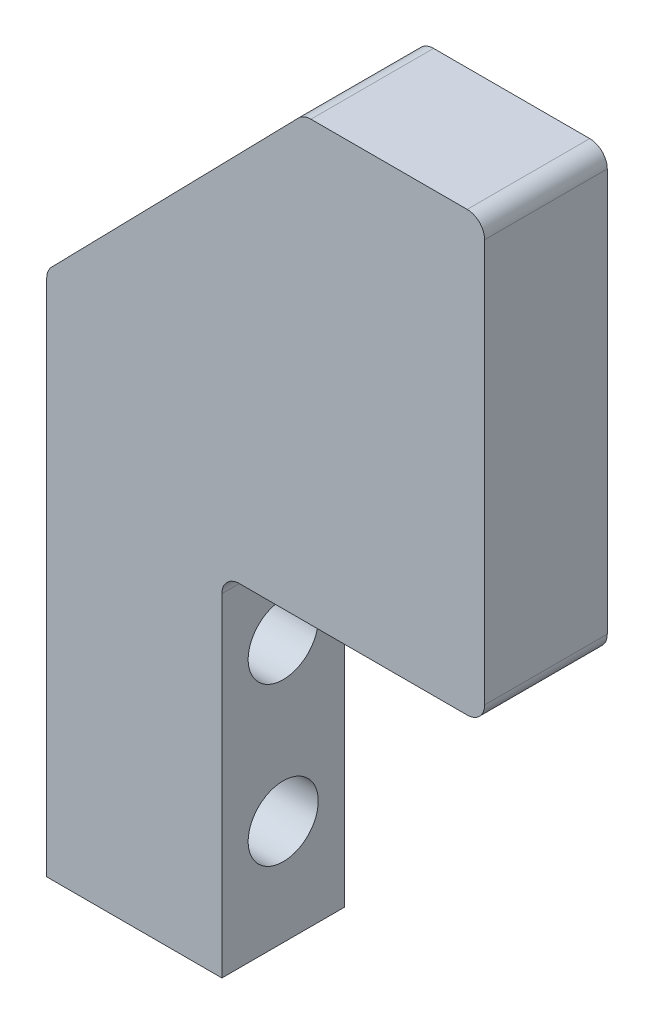
SolidWorks part; units mm, degrees
ref_plane "Front Plane" through (0, 0, 0) normal (0, 0, 1) x (1, 0, 0)
ref_plane "Top Plane" through (0, 0, 0) normal (0, 1, 0) x (1, 0, 0)
ref_plane "Right Plane" through (0, 0, 0) normal (1, 0, 0) x (0, 0, -1)
sketch "Sketch1" plane through (0, 0, 0) normal (0, 0, 1) x (1, 0, 0)
  line L0 (-187.207, 37.0865) -> (-187.207, -258.8379)
  line L1 (-36.3759, 191.1621) -> (52.793, 191.1621)
  line L3 (-187.207, -258.8379) -> (-87.207, -258.8379)
  line L4 (62.793, 181.1621) -> (62.793, -48.8379)
  line L5 (-87.207, -258.8379) -> (-87.207, -68.8379)
  line L6 (-77.207, -58.8379) -> (52.793, -58.8379)
  line L9 (-43.527, 188.1522) -> (-184.3582, 44.0766)
  arc A0 (62.793, 181.1621) -> (52.793, 191.1621) centre (52.793, 181.1621) ccw
  arc A1 (52.793, -58.8379) -> (62.793, -48.8379) centre (52.793, -48.8379) ccw
  arc A2 (-87.207, -68.8379) -> (-77.207, -58.8379) centre (-77.207, -68.8379) cw
  arc A3 (-187.207, 37.0865) -> (-184.3582, 44.0766) centre (-177.207, 37.0865) cw
  arc A4 (-43.527, 188.1522) -> (-36.3759, 191.1621) centre (-36.3759, 181.1621) cw
extrude "Boss-Extrude1" add sketch "Sketch1" along normal blind 70
sketch "Sketch2" plane through (-87.207, 0, 0) normal (1, 0, 0) x (0, 0, -1)
  circle A0 centre (-35, -108.8379) radius 20
  circle A1 centre (-35, -198.8379) radius 20
extrude "Cut-Extrude1" cut sketch "Sketch2" against normal blind 129
sketch "Sketch3" plane through (0, 0, 70) normal (0, 0, 1) x (1, 0, 0)
  line L0 (62.793, 165.6063) -> (62.793, 165.5345)
  line L1 (62.793, 179.5345) -> (62.793, 172.5345)
  line L2 (62.793, 151.6063) -> (62.793, 151.5345)
  line L3 (62.793, 158.6063) -> (62.793, 158.5345)
  line L4 (62.793, 144.6063) -> (62.793, 144.5345)
  line L5 (62.793, 137.6063) -> (62.793, 137.5345)
  line L6 (62.793, 130.6063) -> (62.793, 130.5345)
  line L7 (62.793, 123.6063) -> (62.793, 123.5345)
  line L8 (62.793, 116.6063) -> (62.793, 116.5345)
  line L9 (62.793, 109.6063) -> (62.793, 109.5345)
  line L10 (62.793, 102.6063) -> (62.793, 102.5345)
  line L12 (62.793, 102.5345) -> (62.793, 97.0704)
  line L13 (62.793, 172.6063) -> (62.793, 172.5345)
  line L14 (62.793, 172.5345) -> (62.793, 165.5345)
  line L15 (62.793, 165.5345) -> (62.793, 158.5345)
  line L16 (62.793, 158.5345) -> (62.793, 151.5345)
  line L17 (62.793, 151.5345) -> (62.793, 144.5345)
  line L18 (62.793, 144.5345) -> (62.793, 137.6063)
  arc A0 (61.793, 177.8024) -> (61.793, 174.3383) centre (62.793, 176.0704) ccw
  arc A1 (61.793, 170.8024) -> (61.793, 167.3383) centre (62.793, 169.0704) ccw
  arc A2 (61.793, 163.8024) -> (61.793, 160.3383) centre (62.793, 162.0704) ccw
  arc A3 (61.793, 156.8024) -> (61.793, 153.3383) centre (62.793, 155.0704) ccw
  arc A4 (61.793, 149.8024) -> (61.793, 146.3383) centre (62.793, 148.0704) ccw
  arc A5 (61.793, 142.8024) -> (61.793, 139.3383) centre (62.793, 141.0704) ccw
  arc A6 (61.793, 135.8024) -> (61.793, 132.3383) centre (62.793, 134.0704) ccw
  arc A7 (61.793, 128.8024) -> (61.793, 125.3383) centre (62.793, 127.0704) ccw
  arc A8 (61.793, 121.8024) -> (61.793, 118.3383) centre (62.793, 120.0704) ccw
  arc A9 (61.793, 114.8024) -> (61.793, 111.3383) centre (62.793, 113.0704) ccw
  arc A10 (61.793, 107.8024) -> (61.793, 104.3383) centre (62.793, 106.0704) ccw
  arc A11 (61.793, 100.8024) -> (62.793, 97.0704) centre (62.793, 99.0704) ccw
  arc A12 (61.793, 177.8024) -> (62.793, 179.5345) centre (60.793, 179.5345) ccw
  arc A13 (62.793, 165.6063) -> (61.793, 167.3383) centre (60.793, 165.6063) ccw
  arc A14 (62.793, 172.5345) -> (61.793, 170.8024) centre (60.793, 172.5345) cw
  arc A15 (61.793, 174.3383) -> (62.793, 172.6063) centre (60.793, 172.6063) cw
  arc A16 (62.793, 165.5345) -> (61.793, 163.8024) centre (60.793, 165.5345) cw
  arc A17 (62.793, 158.6063) -> (61.793, 160.3383) centre (60.793, 158.6063) ccw
  arc A18 (62.793, 158.5345) -> (61.793, 156.8024) centre (60.793, 158.5345) cw
  arc A19 (62.793, 151.6063) -> (61.793, 153.3383) centre (60.793, 151.6063) ccw
  arc A20 (61.793, 149.8024) -> (62.793, 151.5345) centre (60.793, 151.5345) ccw
  arc A21 (61.793, 146.3383) -> (62.793, 144.6063) centre (60.793, 144.6063) cw
  arc A22 (61.793, 142.8024) -> (62.793, 144.5345) centre (60.793, 144.5345) ccw
  arc A23 (62.793, 137.6063) -> (61.793, 139.3383) centre (60.793, 137.6063) ccw
  arc A24 (61.793, 135.8024) -> (62.793, 137.5345) centre (60.793, 137.5345) ccw
  arc A25 (62.793, 130.6063) -> (61.793, 132.3383) centre (60.793, 130.6063) ccw
  arc A26 (61.793, 128.8024) -> (62.793, 130.5345) centre (60.793, 130.5345) ccw
  arc A27 (62.793, 123.6063) -> (61.793, 125.3383) centre (60.793, 123.6063) ccw
  arc A28 (61.793, 121.8024) -> (62.793, 123.5345) centre (60.793, 123.5345) ccw
  arc A29 (62.793, 116.6063) -> (61.793, 118.3383) centre (60.793, 116.6063) ccw
  arc A30 (61.793, 114.8024) -> (62.793, 116.5345) centre (60.793, 116.5345) ccw
  arc A31 (62.793, 109.6063) -> (61.793, 111.3383) centre (60.793, 109.6063) ccw
  arc A32 (62.793, 109.5345) -> (61.793, 107.8024) centre (60.793, 109.5345) cw
  arc A33 (62.793, 102.6063) -> (61.793, 104.3383) centre (60.793, 102.6063) ccw
  arc A34 (62.793, 102.5345) -> (61.793, 100.8024) centre (60.793, 102.5345) cw
  point P47 (62.793, 171.0704)
  point P50 (62.793, 174.0704)
